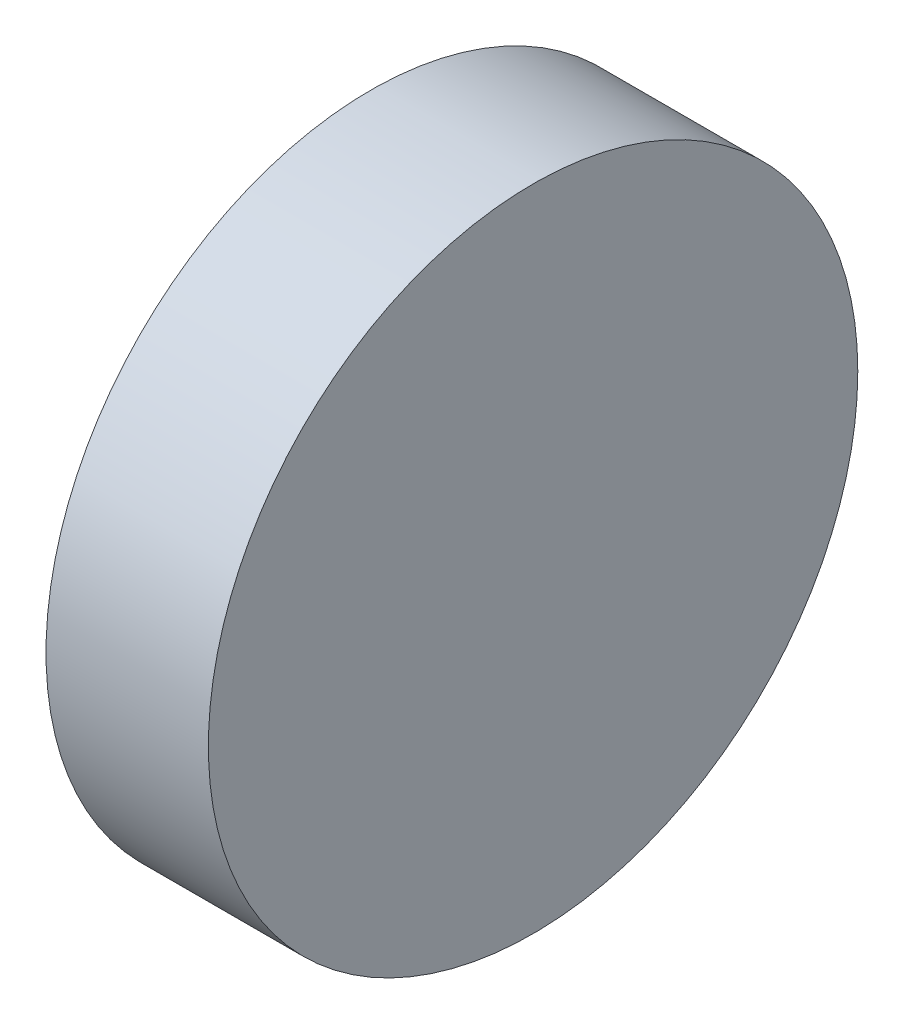
SolidWorks part; units mm, degrees
ref_plane "Front Plane" through (0, 0, 0) normal (0, 0, 1) x (1, 0, 0)
ref_plane "Top Plane" through (0, 0, 0) normal (0, 1, 0) x (1, 0, 0)
ref_plane "Right Plane" through (0, 0, 0) normal (1, 0, 0) x (0, 0, -1)
sketch "Sketch1" plane through (0, 0, 0) normal (1, 0, 0) x (0, 0, -1)
  circle A0 centre (0, 0) radius 25.4
  dimension "D1" = 50.8
extrude "Boss-Extrude1" add sketch "Sketch1" along normal blind 12.7
